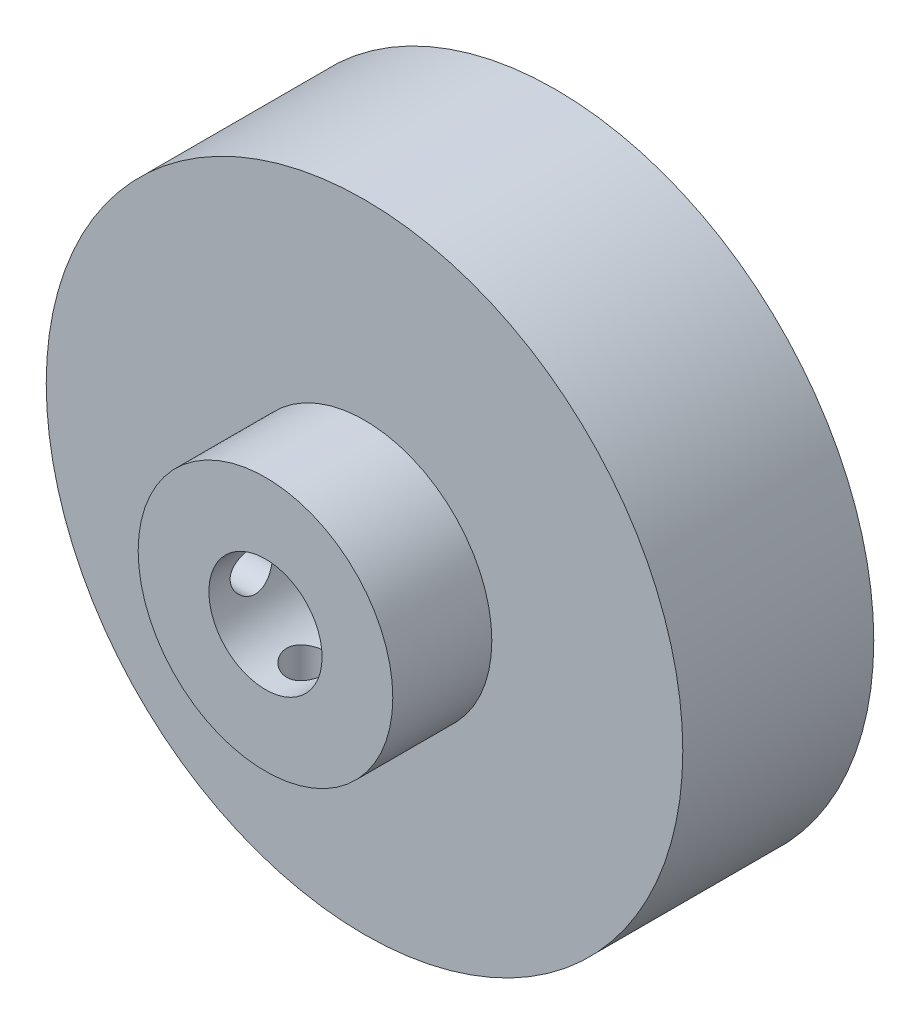
SolidWorks part; units mm, degrees
material "1060 합금"
ref_plane "정면" through (0, 0, 0) normal (0, 0, 1) x (1, 0, 0)
ref_plane "윗면" through (0, 0, 0) normal (0, 1, 0) x (1, 0, 0)
ref_plane "우측면" through (0, 0, 0) normal (1, 0, 0) x (0, 0, -1)
sketch "스케치1" plane through (0, 0, 0) normal (0, 0, 1) x (1, 0, 0)
  circle A0 centre (0, 0) radius 22.5
  dimension "D1" = 45
extrude "보스-돌출1" add sketch "스케치1" along normal blind 13.5
sketch "스케치2" plane through (0, 0, 13.5) normal (0, 0, 1) x (1, 0, 0)
  circle A0 centre (0, 0) radius 9
  dimension "D1" = 18
extrude "보스-돌출2" add sketch "스케치2" along normal blind 7
sketch "스케치3" plane through (0, 0, 20.5) normal (0, 0, 1) x (1, 0, 0)
  circle A0 centre (0, 0) radius 4
  dimension "D1" = 8
extrude "컷-돌출1" cut sketch "스케치3" against normal through all
sketch "스케치4" plane through (0, 0, 0) normal (0, 1, 0) x (1, 0, 0)
  line L0 (0, 0) -> (0, -20.5) construction
  line L1 (-9, -20.5) -> (9, -20.5) construction
  circle A0 centre (0, -17.5) radius 1.5
  dimension "D1" = 3
  dimension "D2" = 3
extrude "컷-돌출2" cut sketch "스케치4" against normal through all
sketch "스케치5" plane through (0, 0, 0) normal (1, 0, 0) x (0, 0, -1)
  line L0 (-13.5, 0) -> (-20.5, 0) construction
  line L1 (-13.5, 9) -> (-13.5, -9) construction
  line L2 (-20.5, 9) -> (-20.5, -9) construction
  circle A0 centre (-17.5, 0) radius 1.5
  dimension "D1" = 3
  dimension "D2" = 3
extrude "컷-돌출3" cut sketch "스케치5" against normal through all
